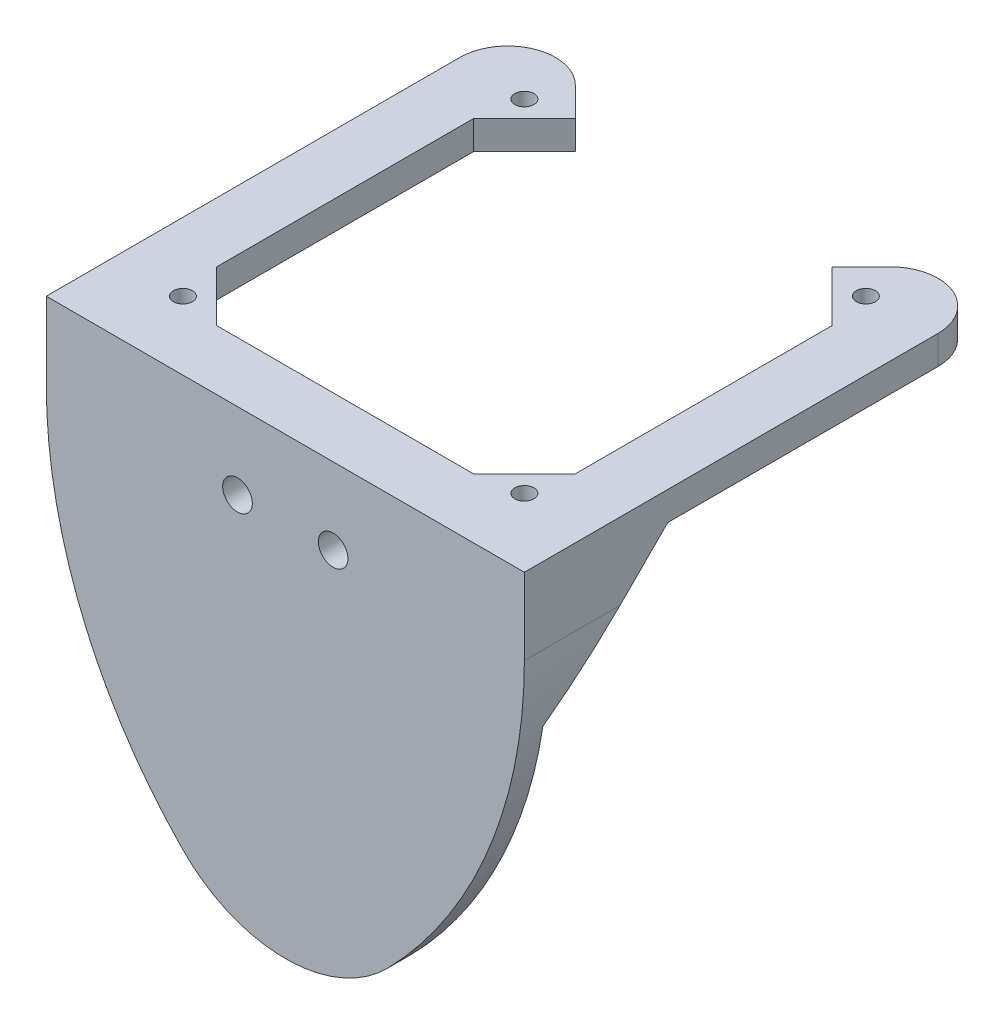
SolidWorks part; units mm, degrees
ref_plane "Front Plane" through (0, 0, 0) normal (0, 0, 1) x (1, 0, 0)
ref_plane "Top Plane" through (0, 0, 0) normal (0, 1, 0) x (1, 0, 0)
ref_plane "Right Plane" through (0, 0, 0) normal (1, 0, 0) x (0, 0, -1)
sketch "Sketch1" plane through (0, 0, 0) normal (0, 1, 0) x (1, 0, 0)
  line L2 (26.8467, 0) -> (37.5, 10.6533)
  line L4 (50, 74.0111) -> (50, -12.5)
  line L8 (37.5, 10.6533) -> (37.5, 64.3467)
  line L9 (37.5, 64.3467) -> (26.8467, 75)
  line L10 (26.8467, 75) -> (32.9289, 81.0822)
  line L11 (26.8467, 0) -> (-26.8467, 0)
  line L12 (0, 0) -> (0, -12.5) construction
  line L13 (-50, -12.5) -> (50, -12.5)
  line L14 (-26.8467, 75) -> (-32.9289, 81.0822)
  line L15 (-37.5, 64.3467) -> (-26.8467, 75)
  line L16 (-37.5, 10.6533) -> (-37.5, 64.3467)
  line L17 (-50, 74.0111) -> (-50, -12.5)
  line L18 (-26.8467, 0) -> (-37.5, 10.6533)
  line L19 (32.1734, 5.3266) -> (35.7089, 1.7911) construction
  line L20 (-32.1734, 5.3266) -> (-35.7089, 1.7911) construction
  line L21 (32.1734, 69.6734) -> (35.7089, 73.2089) construction
  line L22 (-32.1734, 69.6734) -> (-35.7089, 73.2089) construction
  line L23 (-37.5, 37.5) -> (-50, 37.5) construction
  arc A0 (32.9289, 81.0822) -> (50, 74.0111) centre (40, 74.0111) cw
  arc A1 (-32.9289, 81.0822) -> (-50, 74.0111) centre (-40, 74.0111) ccw
  circle A2 centre (35.7089, 1.7911) radius 2
  circle A3 centre (-35.7089, 1.7911) radius 2
  circle A4 centre (35.7089, 73.2089) radius 2
  circle A5 centre (-35.7089, 73.2089) radius 2
  dimension "D5" = 4
  dimension "D7" = 10
  dimension "D1" = 75
  dimension "D2" = 45
  dimension "D3" = 91
  dimension "D4" = 101
  dimension "D6" = 100
extrude "Boss-Extrude1" add sketch "Sketch1" along normal blind 6
sketch "Sketch2" plane through (0, 0, 0) normal (0, -1, 0) x (1, 0, 0)
  line L0 (-50, 12.5) -> (50, 12.5) construction
  line L1 (-37.3255, -70.4089) -> (-38.9421, -73.2089)
  line L2 (-38.9421, -73.2089) -> (-37.3255, -76.0089)
  line L3 (-37.3255, -76.0089) -> (-34.0923, -76.0089)
  line L4 (-34.0923, -76.0089) -> (-32.4757, -73.2089)
  line L5 (-32.4757, -73.2089) -> (-34.0923, -70.4089)
  line L6 (-34.0923, -70.4089) -> (-37.3255, -70.4089)
  line L7 (-38.9421, -1.7911) -> (-37.3255, -4.5911)
  line L8 (-37.3255, -4.5911) -> (-34.0923, -4.5911)
  line L9 (-34.0923, -4.5911) -> (-32.4757, -1.7911)
  line L10 (-32.4757, -1.7911) -> (-34.0923, 1.0089)
  line L11 (-34.0923, 1.0089) -> (-37.3255, 1.0089)
  line L12 (-37.3255, 1.0089) -> (-38.9421, -1.7911)
  line L13 (34.0923, 1.0089) -> (32.4757, -1.7911)
  line L14 (32.4757, -1.7911) -> (34.0923, -4.5911)
  line L15 (34.0923, -4.5911) -> (37.3255, -4.5911)
  line L16 (37.3255, -4.5911) -> (38.9421, -1.7911)
  line L17 (38.9421, -1.7911) -> (37.3255, 1.0089)
  line L18 (37.3255, 1.0089) -> (34.0923, 1.0089)
  line L19 (32.4757, -73.2089) -> (34.0923, -76.0089)
  line L20 (34.0923, -76.0089) -> (37.3255, -76.0089)
  line L21 (37.3255, -76.0089) -> (38.9421, -73.2089)
  line L22 (38.9421, -73.2089) -> (37.3255, -70.4089)
  line L23 (37.3255, -70.4089) -> (34.0923, -70.4089)
  line L24 (34.0923, -70.4089) -> (32.4757, -73.2089)
  circle A0 centre (-35.7089, -73.2089) radius 2.8 construction
  circle A1 centre (-35.7089, -1.7911) radius 2.8 construction
  circle A2 centre (35.7089, -1.7911) radius 2.8 construction
  circle A3 centre (35.7089, -73.2089) radius 2.8 construction
  dimension "D1" = 5.6
extrude "Cut-Extrude1" cut sketch "Sketch2" against normal blind 2.3
sketch "Sketch3" plane through (0, 0, 12.5) normal (0, 0, 1) x (1, 0, 0)
  line L0 (-50, 0) -> (50, 0)
  line L1 (50, 0) -> (50, -10)
  line L2 (-50, -10) -> (-50, 0)
  line L3 (0, -58.9898) -> (0, -10) construction
  line L4 (10, -10) -> (-10, -10) construction
  arc A0 (50, -10) -> (21.4286, -79.9854) centre (-50, -10) cw
  arc A1 (21.4286, -79.9854) -> (-21.4286, -79.9854) centre (0, -58.9898) cw
  arc A3 (-21.4286, -79.9854) -> (-50, -10) centre (50, -10) cw
  circle A4 centre (10, -10) radius 3.1
  circle A5 centre (-10, -10) radius 3.1
  point P11 (-22.5501, -10)
  dimension "D2" = 6.2
  dimension "D3" = 30
  dimension "D4" = 100
  dimension "D1" = 10
  dimension "D5" = 20
extrude "Boss-Extrude2" add sketch "Sketch3" against normal blind 5
sketch "Sketch4" plane through (0, 0, 7.5) normal (0, 0, -1) x (-1, 0, 0)
  line L1 (-10, -4.111) -> (-15.1, -7.0555)
  line L2 (-15.1, -7.0555) -> (-15.1, -12.9445)
  line L3 (-15.1, -12.9445) -> (-10, -15.889)
  line L4 (-10, -15.889) -> (-4.9, -12.9445)
  line L5 (-4.9, -12.9445) -> (-4.9, -7.0555)
  line L6 (-4.9, -7.0555) -> (-10, -4.111)
  line L7 (-50, 0) -> (50, 0) construction
  line L8 (-20.889, -10) -> (-20.889, 0)
  line L9 (-23.776, -20.889) -> (-2.587, -20.889) construction
  line L10 (0, 0) -> (-20.889, 0)
  line L11 (0, -88.9898) -> (0, -20.889) construction
  line L13 (20.889, -10) -> (20.889, 0)
  line L14 (0, 0) -> (20.889, 0)
  line L15 (4.9, -7.0555) -> (10, -4.111)
  line L16 (4.9, -12.9445) -> (4.9, -7.0555)
  line L17 (10, -15.889) -> (4.9, -12.9445)
  line L18 (15.1, -12.9445) -> (10, -15.889)
  line L19 (15.1, -7.0555) -> (15.1, -12.9445)
  line L20 (10, -4.111) -> (15.1, -7.0555)
  circle A0 centre (-10, -10) radius 5.1 construction
  arc A1 (-20.889, -10) -> (-4.7872, -19.5602) centre (-10, -10) ccw
  circle A2 centre (-10, -10) radius 3.1 construction
  arc A3 (-21.4286, -79.9854) -> (21.4286, -79.9854) centre (0, -58.9898) ccw construction
  arc A4 (20.889, -10) -> (4.7872, -19.5602) centre (10, -10) cw
  arc A5 (4.7872, -19.5602) -> (-4.7872, -19.5602) centre (0, -28.3398) ccw
  point P10 (0, 0)
  dimension "D1" = 10.2
  dimension "D2" = 5
  dimension "D3" = 10
extrude "Boss-Extrude3" add sketch "Sketch4" along normal blind 5
fillet "Fillet1" radius 7.5 2 edges at (20.889, 0, 5) (-20.889, 0, 5)
sketch "Sketch5" plane through (50, 0, 0) normal (1, 0, 0) x (0, 0, -1)
  line L0 (17.5, 0) -> (-7.5, 0)
  line L1 (-7.5, 0) -> (74.0111, 0) construction
  line L2 (-7.5, 0) -> (-7.5, -25)
  line L3 (-7.5, -25) -> (17.5, 0)
  dimension "D1" = 25
extrude "Boss-Extrude4" add sketch "Sketch5" against normal blind 5
mirror "Mirror1" about plane through (0, 0, 0) normal (1, 0, 0) of "Boss-Extrude4"
sketch "Sketch6" plane through (0, 0, 7.5) normal (0, 0, 1) x (1, 0, 0)
  line L2 (50, -25) -> (50, -10)
  line L3 (48.8686, -25) -> (50, -25)
  line L4 (50, -25) -> (50, -10)
  line L5 (48.8686, -25) -> (50, -25)
  line L6 (-50, -10) -> (-50, -25)
  line L7 (-50, -25) -> (-48.8686, -25)
  line L8 (-50, -10) -> (-50, -25)
  line L9 (-50, -25) -> (-48.8686, -25)
  arc A1 (48.8686, -25) -> (50, -10) centre (-50, -10) ccw
  arc A2 (48.8686, -25) -> (50, -10) centre (-50, -10) ccw
  arc A3 (-50, -10) -> (-48.8686, -25) centre (50, -10) ccw
  arc A4 (-50, -10) -> (-48.8686, -25) centre (50, -10) ccw
  dimension "D1" = 0
  dimension "D2" = 0
extrude "Cut-Extrude2" cut sketch "Sketch6" against normal up to next
